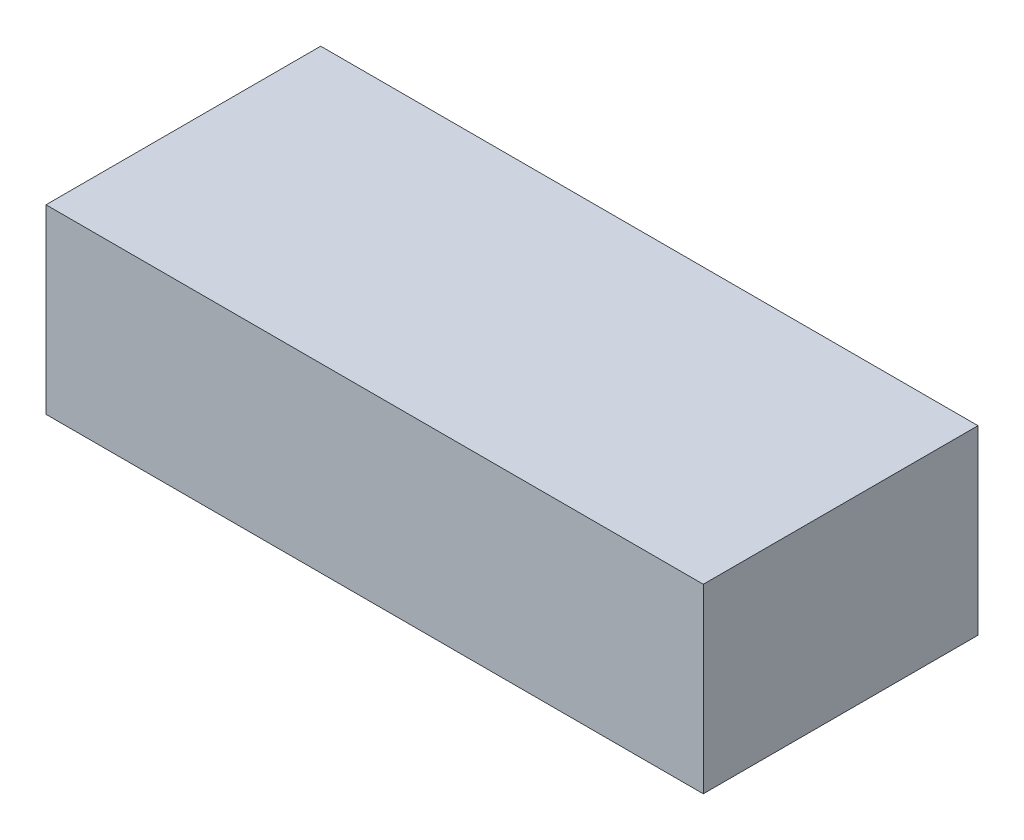
SolidWorks part; units mm, degrees
ref_plane "前视基准面" through (0, 0, 0) normal (0, 0, 1) x (1, 0, 0)
ref_plane "上视基准面" through (0, 0, 0) normal (0, 1, 0) x (1, 0, 0)
ref_plane "右视基准面" through (0, 0, 0) normal (1, 0, 0) x (0, 0, -1)
other "Configuration Table"
sketch "草图1" plane through (0, 0, 0) normal (0, 0, 1) x (1, 0, 0)
  line L1 (-67, 18.5) -> (67, 18.5)
  line L2 (-67, 18.5) -> (-67, -18.5)
  line L3 (-67, -18.5) -> (67, -18.5)
  line L4 (67, 18.5) -> (67, -18.5)
  line L5 (0, -18.5) -> (0, 18.5) construction
  line L6 (-67, 0) -> (67, 0) construction
  point P0 (0, 0)
  dimension "D1" = 37
  dimension "D2" = 134
extrude "凸台-拉伸1" add sketch "草图1" along normal blind 56
